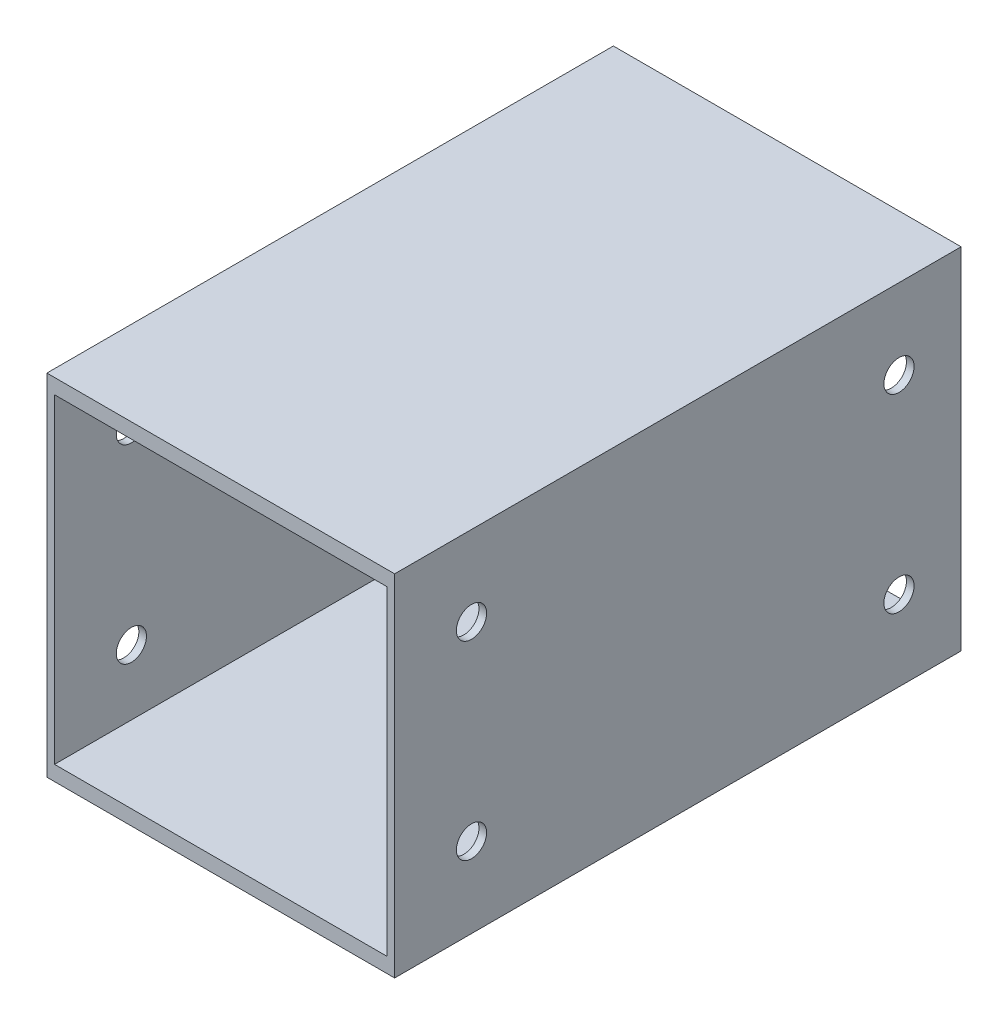
SolidWorks part; units mm, degrees
ref_plane "Alzado" through (0, 0, 0) normal (0, 0, 1) x (1, 0, 0)
ref_plane "Planta" through (0, 0, 0) normal (0, 1, 0) x (1, 0, 0)
ref_plane "Vista lateral" through (0, 0, 0) normal (1, 0, 0) x (0, 0, -1)
sketch "Croquis1" plane through (0, 0, 0) normal (0, 0, 1) x (1, 0, 0)
  line L5 (-22.225, -21.3969) -> (22.225, -21.3969)
  line L6 (-22.225, -21.3969) -> (-22.225, 21.3969)
  line L11 (-22.225, 21.3969) -> (22.225, 21.3969)
  line L12 (22.225, -21.3969) -> (22.225, 21.3969)
  line L17 (-22.225, -21.3969) -> (22.225, 21.3969) construction
  line L18 (-22.225, 21.3969) -> (22.225, -21.3969) construction
  line L19 (-22.225, -21) -> (22.225, -21)
  line L20 (-22.225, -21) -> (-22.225, 21)
  line L21 (-22.225, 21) -> (22.225, 21)
  line L22 (22.225, -21) -> (22.225, 21)
  line L23 (-23.2458, -23.3971) -> (23.2458, -23.3971)
  line L24 (-23.2458, -23.3971) -> (-23.2458, 23.3971)
  line L25 (-23.2458, 23.3971) -> (23.2458, 23.3971)
  line L26 (23.2458, -23.3971) -> (23.2458, 23.3971)
  line L27 (-23.2458, -23.3971) -> (23.2458, 23.3971) construction
  line L28 (-23.2458, 23.3971) -> (23.2458, -23.3971) construction
  point P0 (0, 0)
  point P6 (0, 0)
  dimension "D1" = 0.3969
  dimension "D2" = 0.3969
  dimension "D3" = 42
  dimension "D4" = 44.45
  dimension "D5" = 0
  dimension "D6" = 0
  dimension "D7" = 2.3971
  dimension "D8" = 1.0208
extrude "Saliente-Extruir1" add sketch "Croquis1" along normal blind 75.7317 contours L23 L26 L25 L24 L12 L5 L6 L11
sketch "Croquis2" plane through (-23.2458, 0, 0) normal (-1, 0, 0) x (0, 1, 0)
  line L0 (0, -75.7317) -> (0, -62.9794) construction
  line L1 (21, 0) -> (21, -7.4605) construction
  line L2 (23.794, -36.8817) -> (-13.0329, -36.8817) construction
  line L4 (-23.3971, -75.7317) -> (23.3971, -75.7317) construction
  circle A0 centre (12.7, -65.4567) radius 2.0193
  circle A1 centre (-12.7, -65.4567) radius 2.0193
  circle A2 centre (-12.7, -8.3067) radius 2.0193
  circle A3 centre (12.7, -8.3067) radius 2.0193
  point P4 (21, 0)
  dimension "D1" = 4.0386
  dimension "D4" = 57.15
  dimension "D2" = 10.275
  dimension "D3" = 8.3
extrude "Cortar-Extruir1" cut sketch "Croquis2" against normal through all
